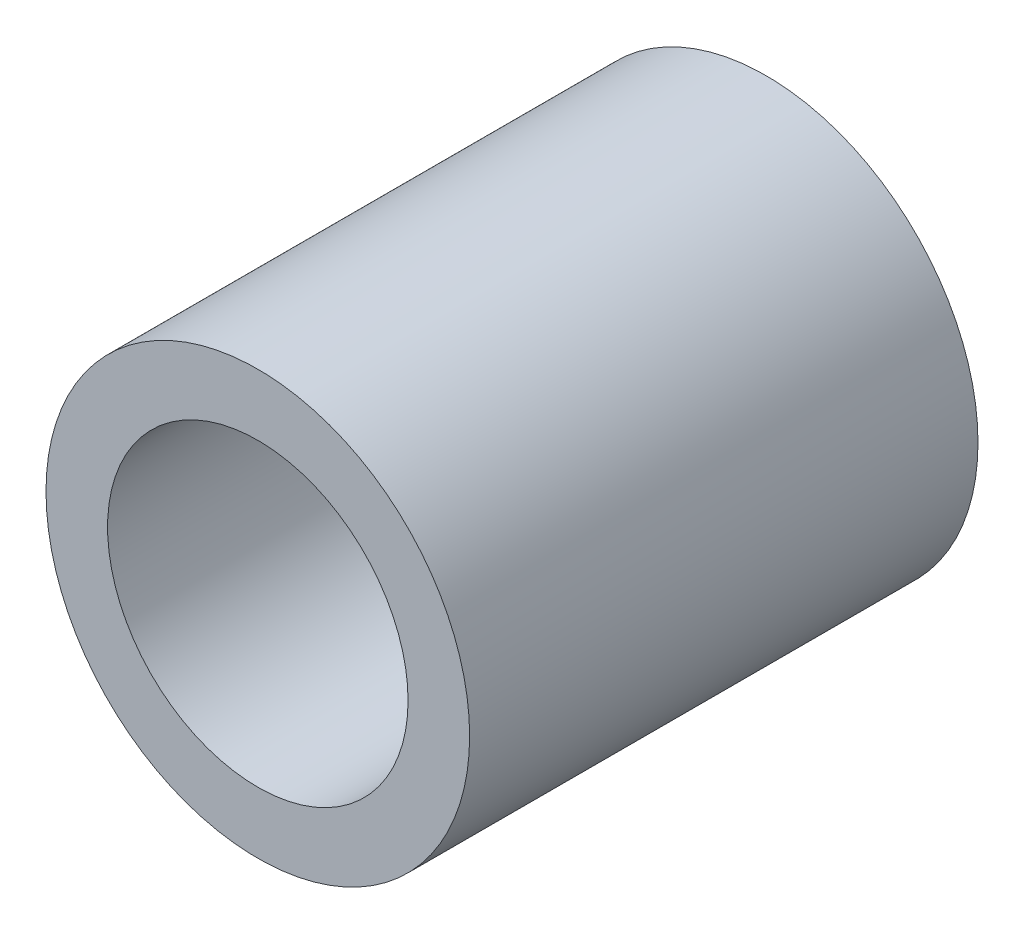
SolidWorks part; units mm, degrees
ref_plane "Front Plane" through (0, 0, 0) normal (0, 0, 1) x (1, 0, 0)
ref_plane "Top Plane" through (0, 0, 0) normal (0, 1, 0) x (1, 0, 0)
ref_plane "Right Plane" through (0, 0, 0) normal (1, 0, 0) x (0, 0, -1)
sketch "Sketch1" plane through (0, 0, 0) normal (0, 0, 1) x (1, 0, 0)
  circle A0 centre (0, 0) radius 4.7625
  circle A1 centre (0, 0) radius 3.3782
  dimension "D1" = 9.525
  dimension "D2" = 6.7564
extrude "Boss-Extrude1" add sketch "Sketch1" along normal blind 11.43
